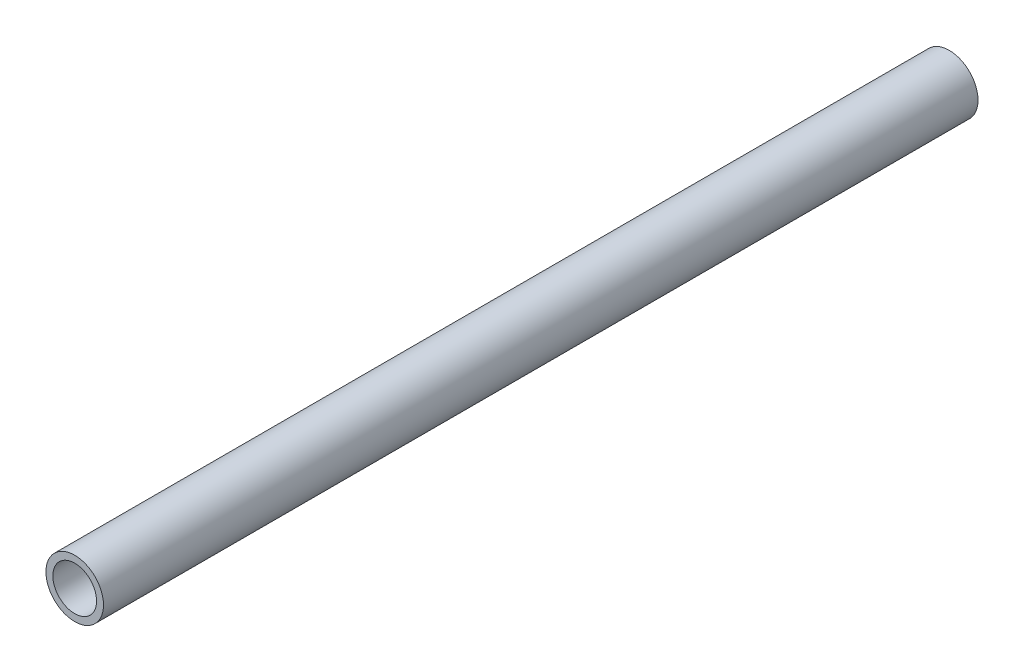
SolidWorks part; units mm, degrees
ref_plane "Front Plane" through (0, 0, 0) normal (0, 0, 1) x (1, 0, 0)
ref_plane "Top Plane" through (0, 0, 0) normal (0, 1, 0) x (1, 0, 0)
ref_plane "Right Plane" through (0, 0, 0) normal (1, 0, 0) x (0, 0, -1)
sketch "Sketch1" plane through (0, 0, 0) normal (0, 0, 1) x (1, 0, 0)
  circle A0 centre (0, 0) radius 12.5
  dimension "D1" = 25
extrude "Extrude-Thin1" add sketch "Sketch1" along normal mid plane 380 thin thin type one direction reverse wall 3
